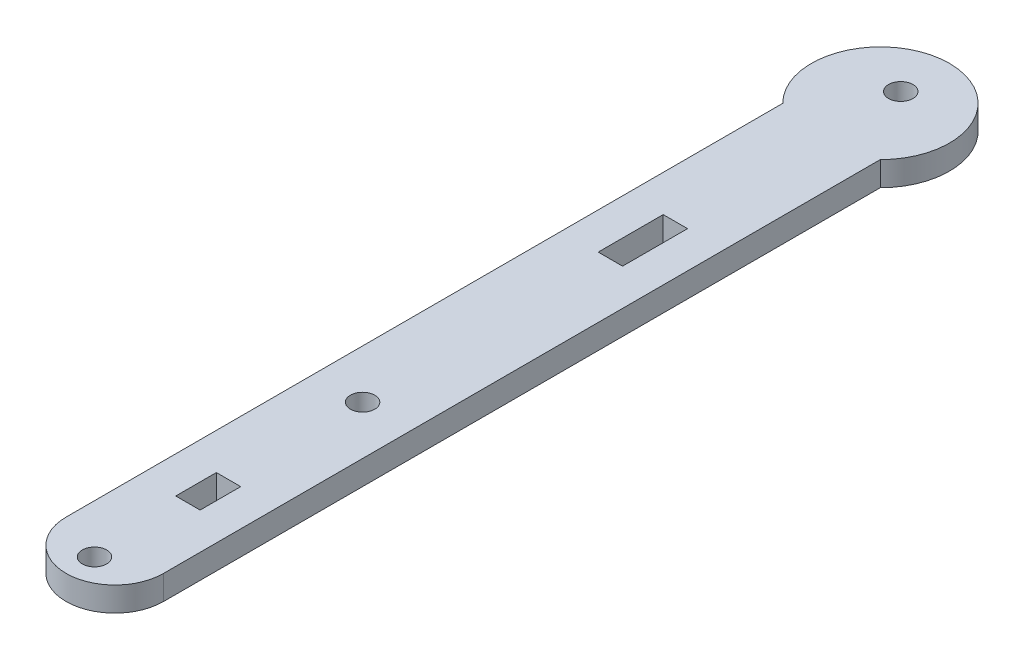
SolidWorks part; units mm, degrees
ref_plane "Alzado" through (0, 0, 0) normal (0, 0, 1) x (1, 0, 0)
ref_plane "Planta" through (0, 0, 0) normal (0, 1, 0) x (1, 0, 0)
ref_plane "Vista lateral" through (0, 0, 0) normal (1, 0, 0) x (0, 0, -1)
sketch "Croquis1" plane through (0, 0, 0) normal (0, 0, 1) x (1, 0, 0)
  line L0 (41807.1733, -434.4395) -> (41807.1733, -346.2199)
  line L1 (41795.1733, -346.2199) -> (41795.1733, -434.4395)
  line L3 (41799.6733, -365.4395) -> (41802.6733, -365.4395)
  line L4 (41799.6733, -365.4395) -> (41799.6733, -373.4395)
  line L5 (41799.6733, -373.4395) -> (41802.6733, -373.4395)
  line L6 (41802.6733, -365.4395) -> (41802.6733, -373.4395)
  line L7 (41799.6733, -420.4395) -> (41802.6733, -420.4395)
  line L8 (41799.6733, -420.4395) -> (41799.6733, -425.4395)
  line L9 (41799.6733, -425.4395) -> (41802.6733, -425.4395)
  line L10 (41802.6733, -420.4395) -> (41802.6733, -425.4395)
  circle A0 centre (41801.1733, -337.6991) radius 1.5
  arc A1 (41807.1733, -346.2199) -> (41795.1733, -346.2199) centre (41801.1733, -340.1991) ccw
  circle A2 centre (41801.1733, -403.9395) radius 1.5
  circle A3 centre (41801.1733, -436.9395) radius 1.5
  arc A4 (41795.1733, -434.4395) -> (41807.1733, -434.4395) centre (41801.1733, -434.4395) ccw
extrude "Saliente-Extruir1" add sketch "Croquis1" along normal blind 3
move or copy body "Sólido-Mover/Copiar1" bodies to move or copy 101 copy no rotation origin (0, -386.0693, 1.5) rotation axis (-1, 0, 0) rotation angle 90
